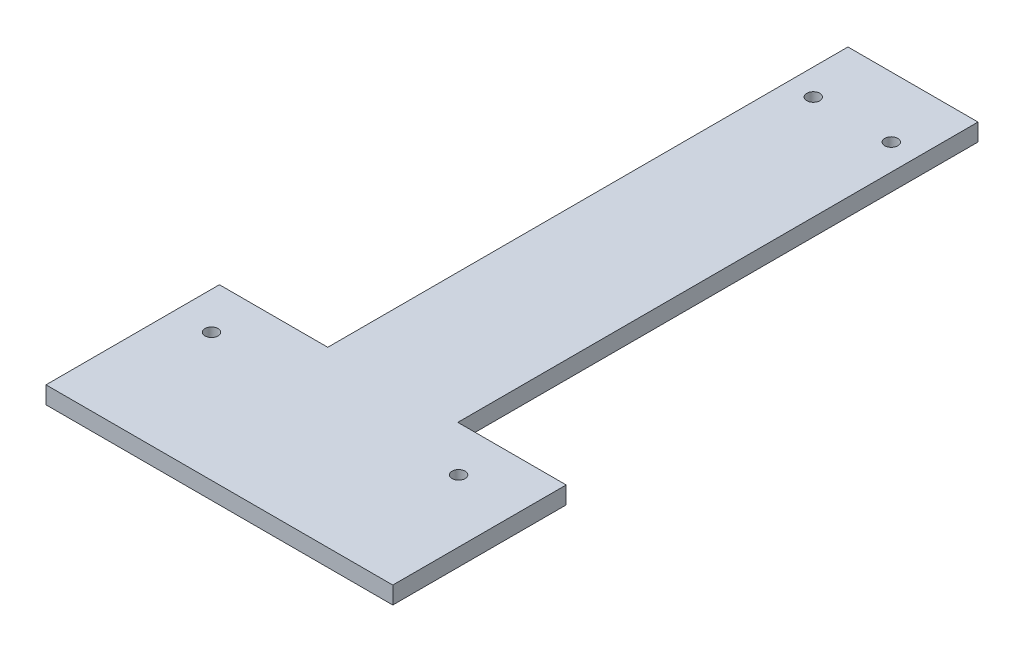
SolidWorks part; units mm, degrees
ref_plane "Front Plane" through (0, 0, 0) normal (0, 0, 1) x (1, 0, 0)
ref_plane "Top Plane" through (0, 0, 0) normal (0, 1, 0) x (1, 0, 0)
ref_plane "Right Plane" through (0, 0, 0) normal (1, 0, 0) x (0, 0, -1)
sketch "Sketch1" plane through (0, 0, 0) normal (0, 0, 1) x (1, 0, 0)
  line L1 (15, 0) -> (0, 0)
  line L2 (15, 0) -> (15, 2)
  line L3 (15, 2) -> (0, 2)
  line L4 (0, 0) -> (0, 2)
  dimension "D1" = 2
  dimension "D2" = 15
extrude "Boss-Extrude1" add sketch "Sketch1" along normal blind 80
sketch "Sketch2" plane through (0, 2, 0) normal (0, 1, 0) x (1, 0, 0)
  line L0 (15, -80) -> (0, -80) construction
  line L1 (27.5, -80) -> (-12.5, -80)
  line L2 (27.5, -80) -> (27.5, -60)
  line L3 (27.5, -60) -> (-12.5, -60)
  line L4 (-12.5, -80) -> (-12.5, -60)
  point P6 (7.5, -80)
  point P7 (7.5, -80)
  dimension "D1" = 40
  dimension "D2" = 20
extrude "Boss-Extrude2" add sketch "Sketch2" against normal blind 2
sketch "Sketch3" plane through (0, 2, 0) normal (0, 1, 0) x (1, 0, 0)
  circle A0 centre (20.2914, -65.2) radius 0.75 construction
  circle A1 centre (20.2914, -65.2) radius 0.75
  circle A2 centre (-8.2086, -65.2) radius 0.75 construction
  circle A3 centre (-8.2086, -65.2) radius 0.75
  circle A4 centre (12, -7) radius 0.75 construction
  circle A5 centre (12, -7) radius 0.75
  circle A6 centre (3, -7) radius 0.75 construction
  circle A7 centre (3, -7) radius 0.75
extrude "Cut-Extrude1" cut sketch "Sketch3" against normal through all
equation "\"ServoGateFixtureHeight\"=80"
equation "\"D1@Boss-Extrude1\"=\"ServoGateFixtureHeight\""
